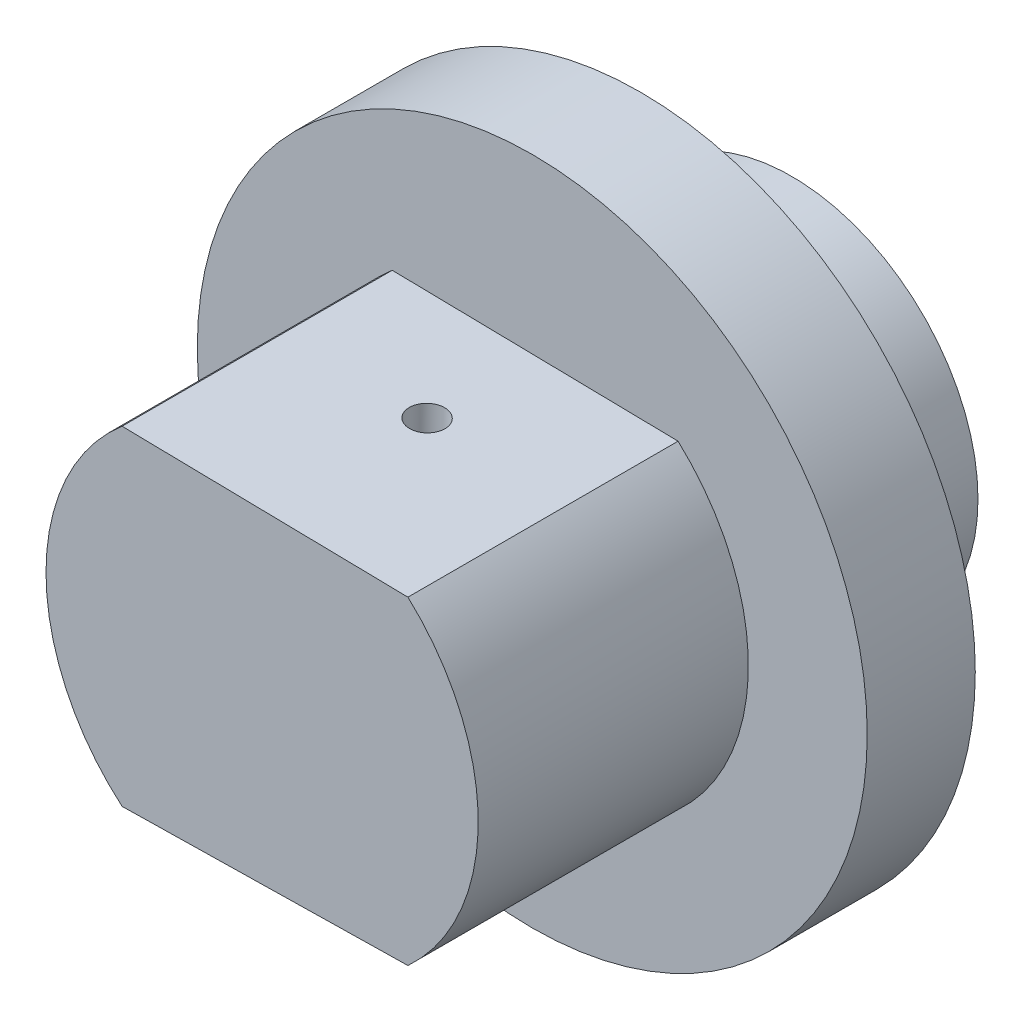
SolidWorks part; units mm, degrees
ref_plane "前视基准面" through (0, 0, 0) normal (0, 0, 1) x (1, 0, 0)
ref_plane "上视基准面" through (0, 0, 0) normal (0, 1, 0) x (1, 0, 0)
ref_plane "右视基准面" through (0, 0, 0) normal (1, 0, 0) x (0, 0, -1)
other "Configuration Table"
sketch "草图1" plane through (0, 0, 0) normal (0, 0, 1) x (1, 0, 0)
  circle A0 centre (0, 0) radius 17.25
  dimension "D1" = 34.5
extrude "凸台-拉伸1" add sketch "草图1" along normal blind 14
sketch "草图2" plane through (0, 0, 14) normal (0, 0, 1) x (1, 0, 0)
  circle A0 centre (0, 0) radius 31
  dimension "D1" = 62
extrude "凸台-拉伸2" add sketch "草图2" along normal blind 10
sketch "草图3" plane through (0, 0, 0) normal (0, 0, -1) x (-1, 0, 0)
  line L1 (-10.5, 10.5) -> (10.5, 10.5)
  line L2 (-10.5, 10.5) -> (-10.5, -10.5)
  line L3 (-10.5, -10.5) -> (10.5, -10.5)
  line L4 (10.5, 10.5) -> (10.5, -10.5)
  line L5 (-10.5, 10.5) -> (10.5, -10.5) construction
  line L6 (-10.5, -10.5) -> (10.5, 10.5) construction
  point P0 (0, 0)
  dimension "D1" = 21
  dimension "D2" = 21
extrude "切除-拉伸1" cut sketch "草图3" against normal through all both and the other way through all
sketch "草图4" plane through (0, 0, 24) normal (0, 0, 1) x (1, 0, 0)
  line L0 (-12.9596, 15.2331) -> (13.4937, 14.7621)
  line L1 (7.7, 0) -> (-7.7, 0) construction
  line L2 (-12.9596, -15.2331) -> (13.4937, -14.7621)
  arc A0 (-12.9596, 15.2331) -> (-12.9596, -15.2331) centre (0, 0) ccw
  arc A1 (13.4937, -14.7621) -> (13.4937, 14.7621) centre (0, 0) ccw
  dimension "D1" = 40
  dimension "D2" = 15
extrude "凸台-拉伸3" add sketch "草图4" along normal blind 20
sketch "草图5" plane through (0, 0, 24) normal (0, 0, -1) x (-1, 0, 0)
  line L1 (-10.5, 10.5) -> (10.5, 10.5)
  line L2 (-10.5, 10.5) -> (-10.5, -10.5)
  line L3 (-10.5, -10.5) -> (10.5, -10.5)
  line L4 (10.5, 10.5) -> (10.5, -10.5)
  line L5 (-10.5, 10.5) -> (10.5, -10.5) construction
  line L6 (-10.5, -10.5) -> (10.5, 10.5) construction
  point P0 (0, 0)
extrude "切除-拉伸2" cut sketch "草图5" against normal blind 20
sketch "草图6" plane through (0.267, 14.9976, 0) normal (0.0178, 0.9998, 0) x (0.9998, -0.0178, 0)
  line L0 (0, -24) -> (0, -44) construction
  line L1 (13.2288, -24) -> (-13.2288, -24) construction
  line L2 (13.2288, -44) -> (-13.2288, -44) construction
  circle A0 centre (0, -34) radius 1.65
  dimension "D1" = 3.3
  dimension "D2" = 10
extrude "切除-拉伸3" cut sketch "草图6" against normal blind 56
sketch "草图8" plane through (0, 0, 44) normal (0, 0, 1) x (1, 0, 0)
  line L2 (-12.9596, -15.2331) -> (13.4937, -14.7621)
  line L3 (13.4937, 14.7621) -> (-12.9596, 15.2331)
  line L4 (-12.9596, -15.2331) -> (13.4937, -14.7621)
  line L5 (13.4937, 14.7621) -> (-12.9596, 15.2331)
  arc A2 (-12.9596, 15.2331) -> (-12.9596, -15.2331) centre (0, 0) ccw
  arc A3 (13.4937, -14.7621) -> (13.4937, 14.7621) centre (0, 0) ccw
  arc A4 (-12.9596, 15.2331) -> (-12.9596, -15.2331) centre (0, 0) ccw
  arc A5 (13.4937, -14.7621) -> (13.4937, 14.7621) centre (0, 0) ccw
  dimension "D1" = 0
extrude "凸台-拉伸4" add sketch "草图8" along normal blind 5
